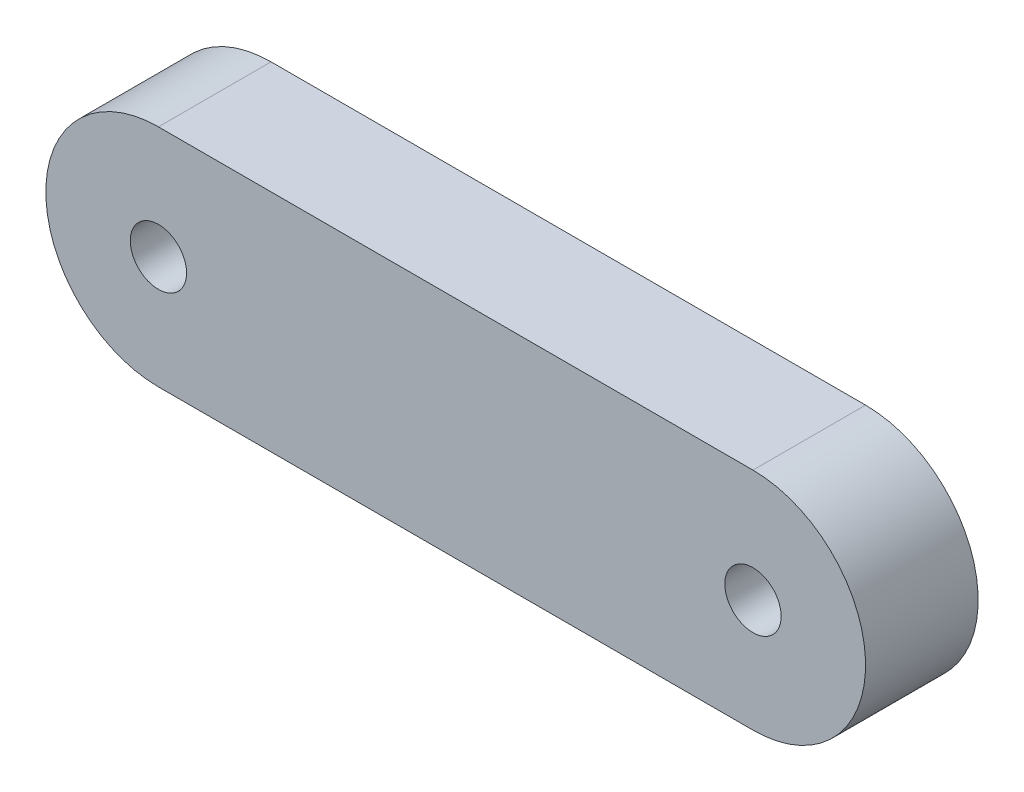
SolidWorks part; units mm, degrees
ref_plane "Front Plane" through (0, 0, 0) normal (0, 0, 1) x (1, 0, 0)
ref_plane "Top Plane" through (0, 0, 0) normal (0, 1, 0) x (1, 0, 0)
ref_plane "Right Plane" through (0, 0, 0) normal (1, 0, 0) x (0, 0, -1)
sketch "Sketch1" plane through (0, 0, 0) normal (0, 0, 1) x (1, 0, 0)
  line L1 (0, 6.35) -> (33.528, 6.35)
  line L2 (0, -6.35) -> (33.528, -6.35)
  circle A0 centre (0, 0) radius 6.35
  circle A1 centre (33.528, 0) radius 6.35
  circle A2 centre (0, 0) radius 1.5875
  circle A3 centre (33.528, 0) radius 1.5875
  dimension "D2" = 12.7
  dimension "D3" = 3.175
  dimension "D1" = 33.528
extrude "Boss-Extrude1" add sketch "Sketch1" along normal blind 6.35 contours A1 L1 A0 L2 | A0 A2 | A1 A3
